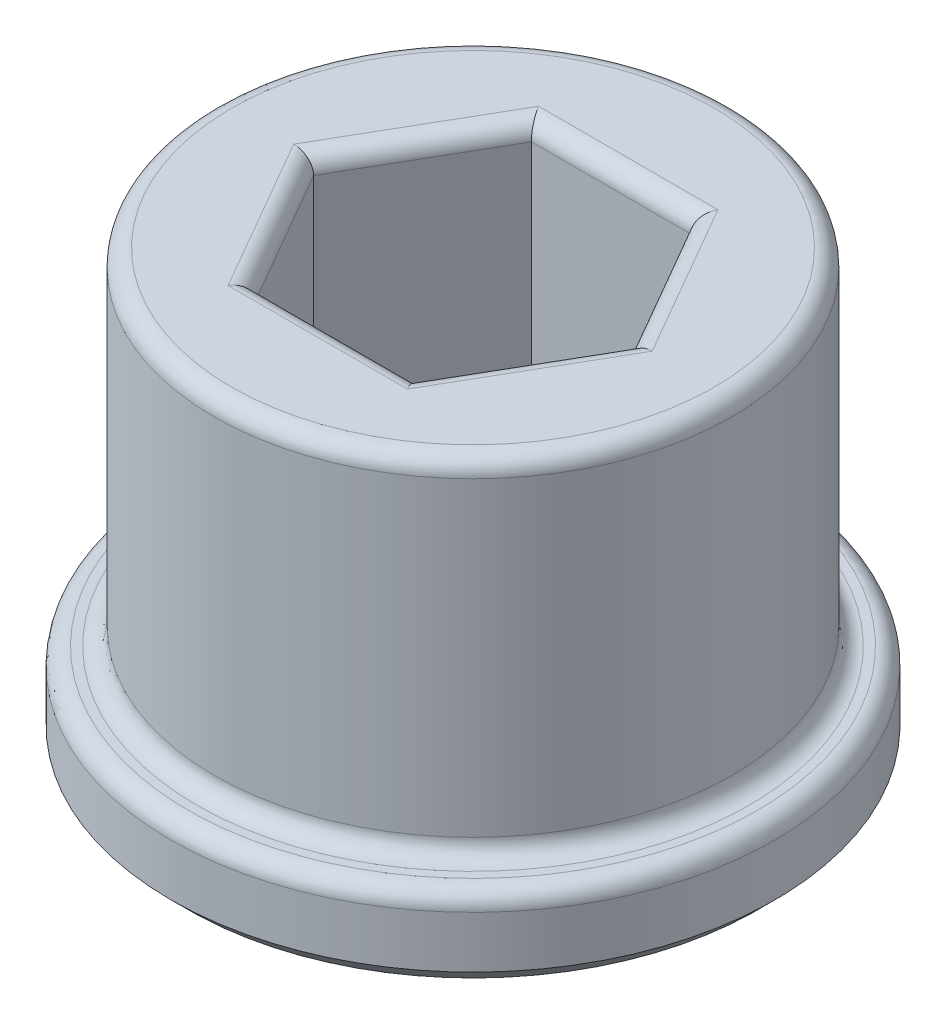
SolidWorks part; units mm, degrees
ref_plane "Front Plane" through (0, 0, 0) normal (0, 0, 1) x (1, 0, 0)
ref_plane "Top Plane" through (0, 0, 0) normal (0, 1, 0) x (1, 0, 0)
ref_plane "Right Plane" through (0, 0, 0) normal (1, 0, 0) x (0, 0, -1)
sketch "Sketch1" plane through (0, 0, 0) normal (0, 1, 0) x (1, 0, 0)
  line L1 (5.8659, 0) -> (2.9329, 5.08)
  line L2 (2.9329, 5.08) -> (-2.9329, 5.08)
  line L3 (-2.9329, 5.08) -> (-5.8659, 0)
  line L4 (-5.8659, 0) -> (-2.9329, -5.08)
  line L5 (-2.9329, -5.08) -> (2.9329, -5.08)
  line L6 (2.9329, -5.08) -> (5.8659, 0)
  circle A0 centre (0, 0) radius 5.08 construction
  circle A1 centre (0, 0) radius 9.525
  dimension "D2" = 19.05
  dimension "D1" = 10.16
extrude "Boss-Extrude1" add sketch "Sketch1" along normal blind 7.9375
sketch "Sketch2" plane through (0, 7.9375, 0) normal (0, 1, 0) x (1, 0, 0)
  line L0 (-2.9329, 5.08) -> (-5.8659, 0)
  line L1 (-5.8659, 0) -> (-2.9329, -5.08)
  line L2 (-2.9329, -5.08) -> (2.9329, -5.08)
  line L3 (2.9329, -5.08) -> (5.8659, 0)
  line L4 (5.8659, 0) -> (2.9329, 5.08)
  line L5 (2.9329, 5.08) -> (-2.9329, 5.08)
  circle A0 centre (0, 0) radius 9.525
  circle A1 centre (0, 0) radius 9.525 construction
extrude "Boss-Extrude2" add sketch "Sketch2" along normal blind 4.7625
sketch "Sketch3" plane through (0, 0, 0) normal (0, -1, 0) x (1, 0, 0)
  line L0 (-2.9329, 5.08) -> (2.9329, 5.08)
  line L2 (2.9329, 5.08) -> (5.8659, 0)
  line L3 (5.8659, 0) -> (2.9329, -5.08)
  line L4 (2.9329, -5.08) -> (-2.9329, -5.08)
  line L5 (-2.9329, -5.08) -> (-5.8659, 0)
  line L6 (-5.8659, 0) -> (-2.9329, 5.08)
  circle A0 centre (0, 0) radius 11.1125
  dimension "D1" = 22.225
extrude "Boss-Extrude3" add sketch "Sketch3" along normal blind 3.175 contours A0
fillet "Fillet1" radius 0.635 2 edges at (0, 0, 9.525) (0, 0, -11.1125)
fillet "Fillet3" radius 0.635 7 edges at (-4.3994, 12.7, 2.54) (0, 12.7, 5.08) (4.3994, 12.7, 2.54) (4.3994, 12.7, -2.54) (0, 12.7, -5.08) (-4.3994, 12.7, -2.54) (0, 12.7, 9.525)
chamfer "Chamfer1" distance 0.635 angle 45 7 edges at (4.3994, -3.175, -2.54) (4.3994, -3.175, 2.54) (0, -3.175, 5.08) (-4.3994, -3.175, 2.54) (-4.3994, -3.175, -2.54) (0, -3.175, -5.08) (0, -3.175, -11.1125)
